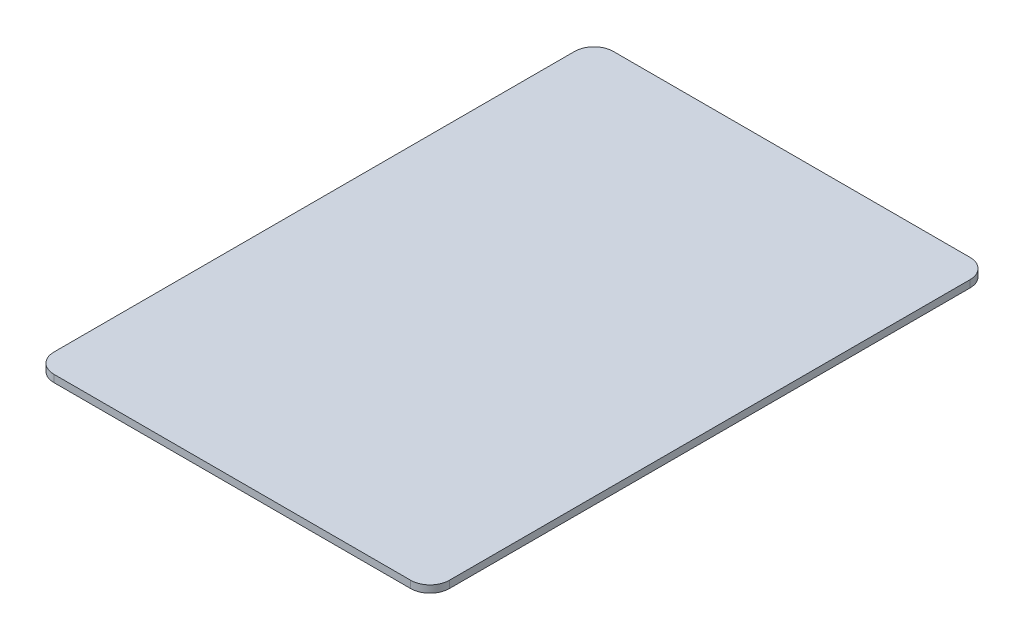
SolidWorks part; units mm, degrees
ref_plane "Front Plane" through (0, 0, 0) normal (0, 0, 1) x (1, 0, 0)
ref_plane "Top Plane" through (0, 0, 0) normal (0, 1, 0) x (1, 0, 0)
ref_plane "Right Plane" through (0, 0, 0) normal (1, 0, 0) x (0, 0, -1)
sketch "Sketch1" plane through (0, 0, 0) normal (0, 1, 0) x (1, 0, 0)
  line L1 (-52.07, -73.66) -> (52.07, -73.66)
  line L2 (-52.07, -73.66) -> (-52.07, 73.66)
  line L3 (-52.07, 73.66) -> (52.07, 73.66)
  line L4 (52.07, -73.66) -> (52.07, 73.66)
  line L5 (-52.07, -73.66) -> (52.07, 73.66) construction
  line L6 (-52.07, 73.66) -> (52.07, -73.66) construction
  point P0 (0, 0)
  dimension "D1" = 147.32
  dimension "D2" = 104.14
extrude "Boss-Extrude1" add sketch "Sketch1" along normal blind 1.905 contours L3 L4 L1 L2
fillet "Fillet1" radius 5.08 4 edges at (-52.07, 0.9525, -73.66) (52.07, 0.9525, -73.66) (-52.07, 0.9525, 73.66) (52.07, 0.9525, 73.66)
